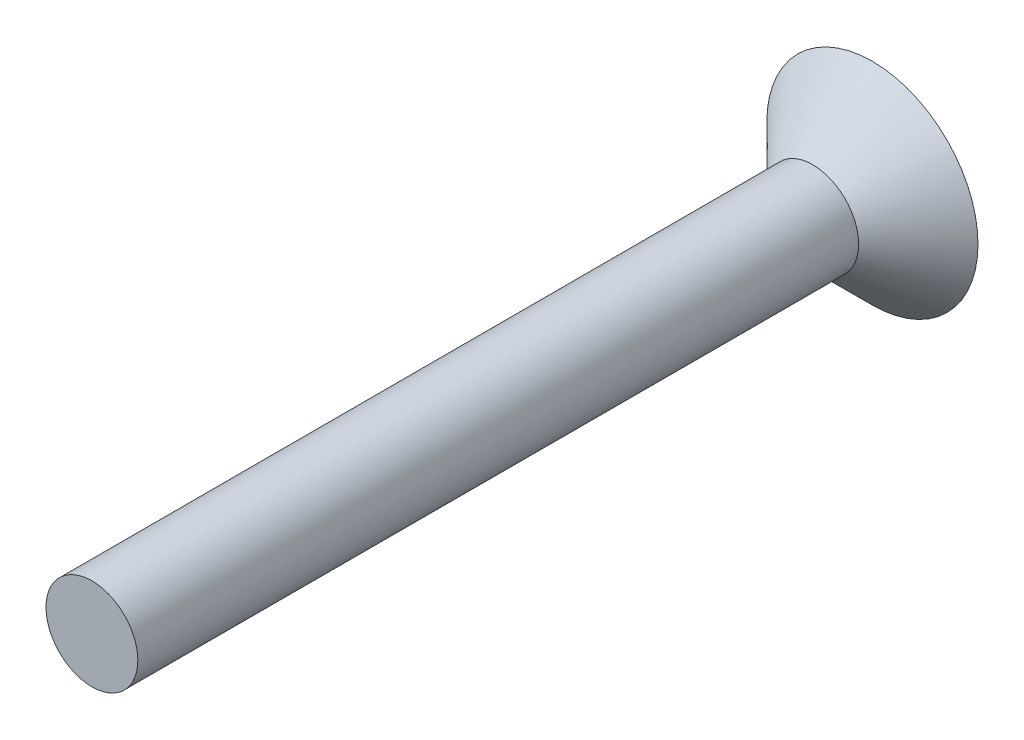
SolidWorks part; units mm, degrees
ref_plane "前视基准面" through (0, 0, 0) normal (0, 0, 1) x (1, 0, 0)
ref_plane "上视基准面" through (0, 0, 0) normal (0, 1, 0) x (1, 0, 0)
ref_plane "右视基准面" through (0, 0, 0) normal (1, 0, 0) x (0, 0, -1)
sketch "草图1" plane through (0, 0, 0) normal (0, 0, 1) x (1, 0, 0)
  circle A0 centre (0, 0) radius 2
  dimension "D1" = 4
extrude "凸台-拉伸1" add sketch "草图1" along normal blind 34 contours A0
sketch "草图2" plane through (0, 0, 0) normal (0, 1, 0) x (1, 0, 0)
  line L3 (2, 0) -> (2, -2.6)
  line L4 (2, -34) -> (2, 0) construction
  line L5 (2, 0) -> (4.6, 0)
  line L6 (2, -2.6) -> (4.6, 0)
  line L7 (0, 0) -> (0, -3.983) construction
  dimension "D1" = 2.6
  dimension "D2" = 2.6
revolve "旋转1" add sketch "草图2" angle 360 about L7
sketch "草图3" plane through (0, 0, 0) normal (0, 0, -1) x (-1, 0, 0)
  line L1 (-0.597, 1.3647) -> (-1.4804, 0.1653)
  line L2 (-1.4804, 0.1653) -> (-0.8834, -1.1994)
  line L3 (-0.8834, -1.1994) -> (0.597, -1.3647)
  line L4 (0.597, -1.3647) -> (1.4804, -0.1653)
  line L5 (1.4804, -0.1653) -> (0.8834, 1.1994)
  line L6 (0.8834, 1.1994) -> (-0.597, 1.3647)
  circle A0 centre (0, 0) radius 1.29 construction
  dimension "D1" = 2.58
extrude "切除-拉伸1" cut sketch "草图3" against normal blind 1.8
